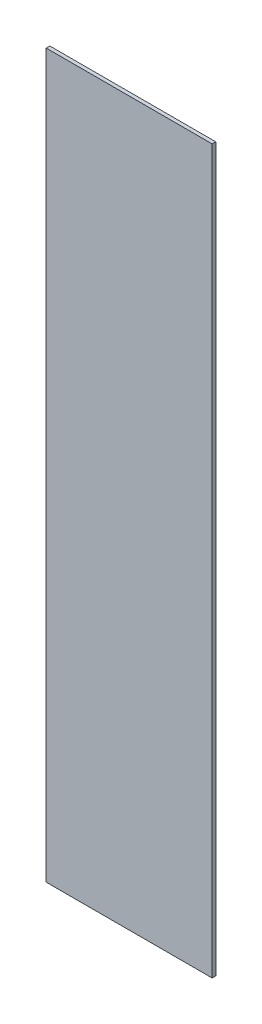
SolidWorks part; units mm, degrees
ref_plane "Front Plane" through (0, 0, 0) normal (0, 0, 1) x (1, 0, 0)
ref_plane "Top Plane" through (0, 0, 0) normal (0, 1, 0) x (1, 0, 0)
ref_plane "Right Plane" through (0, 0, 0) normal (1, 0, 0) x (0, 0, -1)
sketch "Sketch1" plane through (0, 0, 0) normal (0, 1, 0) x (1, 0, 0)
  line L1 (-45.93, 1) -> (45.93, 1)
  line L2 (-45.93, 1) -> (-45.93, -1)
  line L3 (-45.93, -1) -> (45.93, -1)
  line L4 (45.93, 1) -> (45.93, -1)
  line L5 (-45.93, 1) -> (45.93, -1) construction
  line L6 (-45.93, -1) -> (45.93, 1) construction
  point P0 (0, 0)
extrude "Boss-Extrude1" add sketch "Sketch1" along normal blind 400
